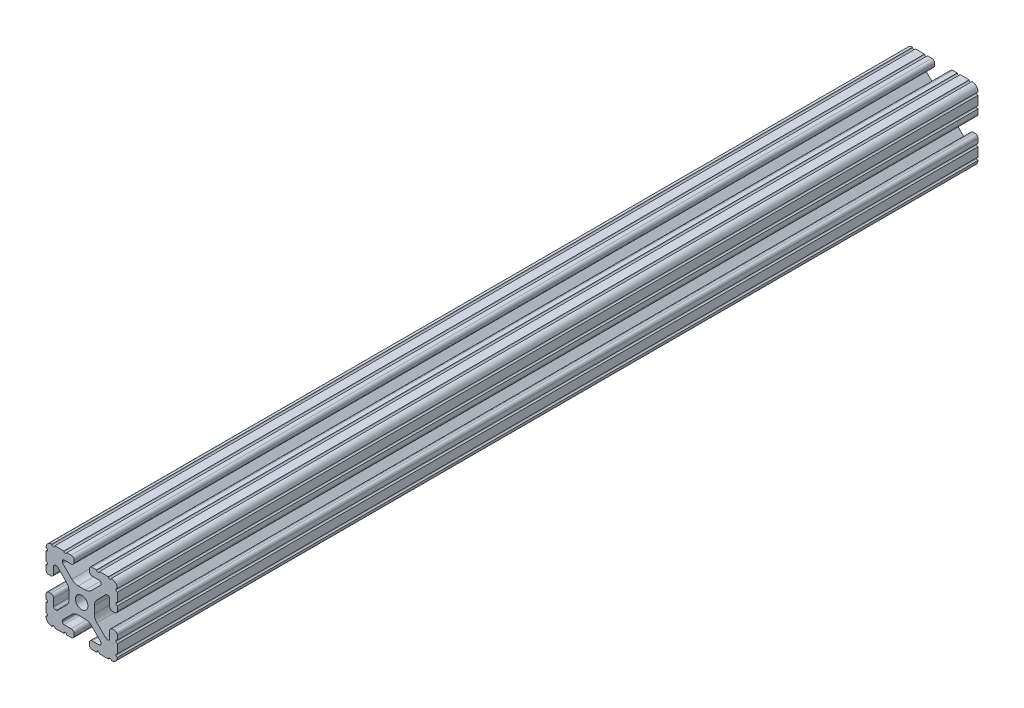
SolidWorks part; units mm, degrees
material "6061 Alloy"
ref_plane "Front Plane" through (0, 0, 0) normal (0, 0, 1) x (1, 0, 0)
ref_plane "Top Plane" through (0, 0, 0) normal (0, 1, 0) x (1, 0, 0)
ref_plane "Right Plane" through (0, 0, 0) normal (1, 0, 0) x (0, 0, -1)
sketch "Sketch1" plane through (0, 0, 0) normal (0, 0, 1) x (1, 0, 0)
  line L0 (0, 25.6181) -> (0, -24.623) construction
  line L1 (-20.8943, 0) -> (20.4607, 0) construction
  line L2 (-10.0229, 12.9148) -> (-5.2522, 8.144)
  line L3 (-10.287, 14.0843) -> (-10.287, 13.5524)
  line L4 (-5.6176, 14.986) -> (-9.3853, 14.986)
  line L5 (-4.064, 17.4964) -> (-4.064, 16.5396)
  line L6 (-7.9742, 19.05) -> (-5.6176, 19.05)
  line L7 (-14.3277, 19.05) -> (-9.4982, 19.05)
  line L8 (-19.05, 9.4961) -> (-19.05, 14.3277)
  line L9 (-19.05, 5.6176) -> (-19.05, 7.9763)
  line L10 (-16.5396, 4.064) -> (-17.4964, 4.064)
  line L11 (-14.986, 9.3853) -> (-14.986, 5.6176)
  line L12 (-13.516, 10.287) -> (-14.0843, 10.287)
  line L13 (-8.1476, 5.2921) -> (-12.8784, 10.0229)
  line L14 (-6.7564, -1.9335) -> (-6.7564, 1.9335)
  line L15 (-12.8784, -10.0229) -> (-8.1476, -5.2921)
  line L16 (-14.0843, -10.287) -> (-13.516, -10.287)
  line L17 (-14.986, -5.6176) -> (-14.986, -9.3853)
  line L18 (-17.4964, -4.064) -> (-16.5396, -4.064)
  line L19 (-19.05, -7.9763) -> (-19.05, -5.6176)
  line L20 (-19.05, -14.3277) -> (-19.05, -9.4961)
  line L21 (-9.4961, -19.05) -> (-14.3277, -19.05)
  line L22 (-5.6176, -19.05) -> (-7.9763, -19.05)
  line L23 (-4.064, -17.4964) -> (-4.064, -16.5396)
  line L24 (10.0229, -12.9148) -> (5.2522, -8.144)
  line L25 (10.287, -14.0843) -> (10.287, -13.5524)
  line L26 (5.6176, -14.986) -> (9.3853, -14.986)
  line L28 (-1.9022, 6.7564) -> (1.9022, 6.7564)
  line L29 (-1.9022, -6.7564) -> (1.9022, -6.7564)
  line L31 (-5.6176, -14.986) -> (-9.3853, -14.986)
  line L32 (-10.287, -14.0843) -> (-10.287, -13.5524)
  line L33 (-10.0229, -12.9148) -> (-5.2522, -8.144)
  line L66 (4.064, -16.5396) -> (4.064, -17.4964)
  line L67 (5.6176, -19.05) -> (7.9763, -19.05)
  line L68 (9.4961, -19.05) -> (14.3277, -19.05)
  line L69 (19.05, -14.3277) -> (19.05, -9.4961)
  line L70 (19.05, -7.9763) -> (19.05, -5.6176)
  line L71 (17.4964, -4.064) -> (16.5396, -4.064)
  line L72 (14.986, -5.6176) -> (14.986, -9.3853)
  line L73 (14.0843, -10.287) -> (13.516, -10.287)
  line L74 (12.8784, -10.0229) -> (8.1476, -5.2921)
  line L75 (6.7564, -1.9335) -> (6.7564, 1.9335)
  line L76 (8.1476, 5.2921) -> (12.8784, 10.0229)
  line L77 (13.516, 10.287) -> (14.0843, 10.287)
  line L78 (14.986, 9.3853) -> (14.986, 5.6176)
  line L79 (16.5396, 4.064) -> (17.4964, 4.064)
  line L80 (19.05, 5.6176) -> (19.05, 7.9763)
  line L81 (19.05, 9.4961) -> (19.05, 14.3277)
  line L82 (14.3277, 19.05) -> (9.4982, 19.05)
  line L83 (7.9742, 19.05) -> (5.6176, 19.05)
  line L84 (4.064, 17.4964) -> (4.064, 16.5396)
  line L85 (5.6176, 14.986) -> (9.3853, 14.986)
  line L86 (10.287, 14.0843) -> (10.287, 13.5524)
  line L87 (10.0229, 12.9148) -> (5.2522, 8.144)
  arc A0 (-10.0229, 12.9148) -> (-10.287, 13.5524) centre (-9.3853, 13.5524) cw
  circle A1 centre (0, 0) radius 3.3274
  arc A2 (-10.287, 14.0843) -> (-9.3853, 14.986) centre (-9.3853, 14.0843) cw
  arc A3 (-4.064, 16.5396) -> (-5.6176, 14.986) centre (-5.6176, 16.5396) cw
  arc A4 (-5.6176, 19.05) -> (-4.064, 17.4964) centre (-5.6176, 17.4964) cw
  arc A5 (-7.9742, 19.05) -> (-9.4982, 19.05) centre (-8.7362, 19.05) cw
  arc A6 (-14.3277, 19.05) -> (-15.8475, 19.05) centre (-15.0876, 18.9933) cw
  arc A7 (-19.05, 15.8475) -> (-15.8475, 19.05) centre (-15.8751, 15.8751) cw
  arc A8 (-19.05, 15.8475) -> (-19.05, 14.3277) centre (-18.9933, 15.0876) cw
  arc A9 (-19.05, 9.4961) -> (-19.05, 7.9763) centre (-18.9933, 8.7362) cw
  arc A10 (-17.4964, 4.064) -> (-19.05, 5.6176) centre (-17.4964, 5.6176) cw
  arc A11 (-14.986, 5.6176) -> (-16.5396, 4.064) centre (-16.5396, 5.6176) cw
  arc A12 (-14.986, 9.3853) -> (-14.0843, 10.287) centre (-14.0843, 9.3853) cw
  arc A13 (-13.516, 10.287) -> (-12.8784, 10.0229) centre (-13.516, 9.3853) cw
  arc A14 (-8.1476, 5.2921) -> (-6.7564, 1.9335) centre (-11.5062, 1.9335) cw
  arc A15 (-6.7564, -1.9335) -> (-8.1476, -5.2921) centre (-11.5062, -1.9335) cw
  arc A16 (-12.8784, -10.0229) -> (-13.516, -10.287) centre (-13.516, -9.3853) cw
  arc A17 (-14.0843, -10.287) -> (-14.986, -9.3853) centre (-14.0843, -9.3853) cw
  arc A18 (-16.5396, -4.064) -> (-14.986, -5.6176) centre (-16.5396, -5.6176) cw
  arc A19 (-19.05, -5.6176) -> (-17.4964, -4.064) centre (-17.4964, -5.6176) cw
  arc A20 (-19.05, -7.9763) -> (-19.05, -9.4961) centre (-18.9933, -8.7362) cw
  arc A21 (-19.05, -14.3277) -> (-19.05, -15.8475) centre (-18.9933, -15.0876) cw
  arc A22 (-15.8475, -19.05) -> (-19.05, -15.8475) centre (-15.8751, -15.8751) cw
  arc A23 (-15.8475, -19.05) -> (-14.3277, -19.05) centre (-15.0876, -18.9933) cw
  arc A24 (-9.4961, -19.05) -> (-7.9763, -19.05) centre (-8.7362, -18.9933) cw
  arc A25 (-4.064, -17.4964) -> (-5.6176, -19.05) centre (-5.6176, -17.4964) cw
  arc A26 (-5.2522, -8.144) -> (-1.9022, -6.7564) centre (-1.9022, -11.494) cw
  arc A27 (1.9022, -6.7564) -> (5.2522, -8.144) centre (1.9022, -11.494) cw
  arc A28 (10.0229, -12.9148) -> (10.287, -13.5524) centre (9.3853, -13.5524) cw
  arc A29 (10.287, -14.0843) -> (9.3853, -14.986) centre (9.3853, -14.0843) cw
  arc A30 (4.064, -16.5396) -> (5.6176, -14.986) centre (5.6176, -16.5396) cw
  arc A31 (-4.064, -16.5396) -> (-5.6176, -14.986) centre (-5.6176, -16.5396) ccw
  arc A32 (-10.287, -14.0843) -> (-9.3853, -14.986) centre (-9.3853, -14.0843) ccw
  arc A33 (-10.0229, -12.9148) -> (-10.287, -13.5524) centre (-9.3853, -13.5524) ccw
  arc A79 (4.064, -17.4964) -> (5.6176, -19.05) centre (5.6176, -17.4964) ccw
  arc A80 (9.4961, -19.05) -> (7.9763, -19.05) centre (8.7362, -18.9933) ccw
  arc A81 (15.8475, -19.05) -> (14.3277, -19.05) centre (15.0876, -18.9933) ccw
  arc A82 (15.8475, -19.05) -> (19.05, -15.8475) centre (15.8751, -15.8751) ccw
  arc A83 (19.05, -14.3277) -> (19.05, -15.8475) centre (18.9933, -15.0876) ccw
  arc A84 (19.05, -7.9763) -> (19.05, -9.4961) centre (18.9933, -8.7362) ccw
  arc A85 (19.05, -5.6176) -> (17.4964, -4.064) centre (17.4964, -5.6176) ccw
  arc A86 (16.5396, -4.064) -> (14.986, -5.6176) centre (16.5396, -5.6176) ccw
  arc A87 (14.0843, -10.287) -> (14.986, -9.3853) centre (14.0843, -9.3853) ccw
  arc A88 (12.8784, -10.0229) -> (13.516, -10.287) centre (13.516, -9.3853) ccw
  arc A89 (6.7564, -1.9335) -> (8.1476, -5.2921) centre (11.5062, -1.9335) ccw
  arc A90 (8.1476, 5.2921) -> (6.7564, 1.9335) centre (11.5062, 1.9335) ccw
  arc A91 (13.516, 10.287) -> (12.8784, 10.0229) centre (13.516, 9.3853) ccw
  arc A92 (14.986, 9.3853) -> (14.0843, 10.287) centre (14.0843, 9.3853) ccw
  arc A93 (14.986, 5.6176) -> (16.5396, 4.064) centre (16.5396, 5.6176) ccw
  arc A94 (17.4964, 4.064) -> (19.05, 5.6176) centre (17.4964, 5.6176) ccw
  arc A95 (19.05, 9.4961) -> (19.05, 7.9763) centre (18.9933, 8.7362) ccw
  arc A96 (19.05, 15.8475) -> (19.05, 14.3277) centre (18.9933, 15.0876) ccw
  arc A97 (19.05, 15.8475) -> (15.8475, 19.05) centre (15.8751, 15.8751) ccw
  arc A98 (14.3277, 19.05) -> (15.8475, 19.05) centre (15.0876, 18.9933) ccw
  arc A99 (7.9742, 19.05) -> (9.4982, 19.05) centre (8.7362, 19.05) ccw
  arc A100 (5.6176, 19.05) -> (4.064, 17.4964) centre (5.6176, 17.4964) ccw
  arc A101 (4.064, 16.5396) -> (5.6176, 14.986) centre (5.6176, 16.5396) ccw
  arc A102 (10.287, 14.0843) -> (9.3853, 14.986) centre (9.3853, 14.0843) ccw
  arc A103 (10.0229, 12.9148) -> (10.287, 13.5524) centre (9.3853, 13.5524) ccw
  arc A104 (1.9022, 6.7564) -> (5.2522, 8.144) centre (1.9022, 11.494) ccw
  arc A105 (-5.2522, 8.144) -> (-1.9022, 6.7564) centre (-1.9022, 11.494) ccw
  dimension "D1" = 6.6548
  dimension "D2" = 19.05
  dimension "D3" = 38.1
  dimension "D4" = 20.574
  dimension "D5" = 13.5128
  dimension "D6" = 4.064
  dimension "D7" = 8.128
  dimension "D8" = 4.064
  dimension "D9" = 12.2936
extrude "Extrude1" add sketch "Sketch1" against normal blind 459.74
